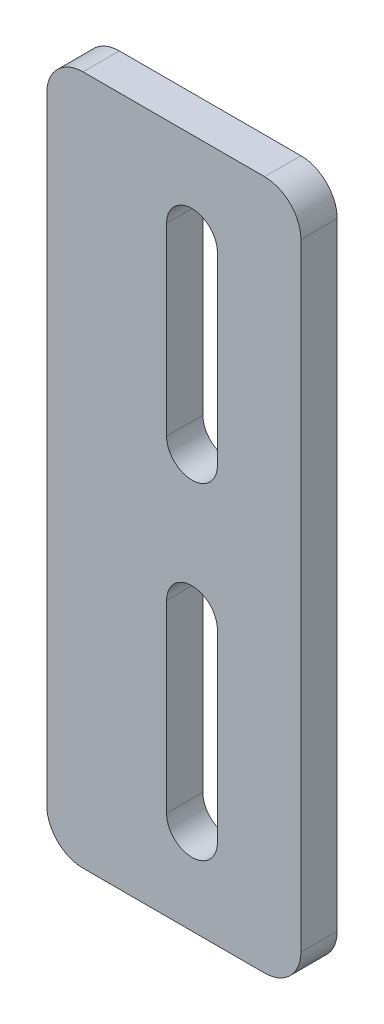
SolidWorks part; units mm, degrees
ref_plane "Front Plane" through (0, 0, 0) normal (0, 0, 1) x (1, 0, 0)
ref_plane "Top Plane" through (0, 0, 0) normal (0, 1, 0) x (1, 0, 0)
ref_plane "Right Plane" through (0, 0, 0) normal (1, 0, 0) x (0, 0, -1)
sketch "Sketch1" plane through (0, 0, 0) normal (0, 0, 1) x (1, 0, 0)
  line L0 (77.5, 30.527) -> (0, 30.527) construction
  line L1 (0, -64.473) -> (35, -64.473)
  line L2 (0, -64.473) -> (0, 30.527)
  line L3 (0, 30.527) -> (35, 30.527)
  line L4 (35, -64.473) -> (35, 30.527)
  line L5 (23.5, -7.173) -> (23.5, 18.227) construction
  line L6 (16.5, 18.227) -> (16.5, -7.173) construction
  line L7 (16.5, -26.773) -> (16.5, -52.173) construction
  line L8 (23.5, -52.173) -> (23.5, -26.773) construction
  line L9 (23.5, -7.173) -> (23.5, 18.227)
  line L10 (16.5, 18.227) -> (16.5, -7.173)
  line L11 (16.5, -26.773) -> (16.5, -52.173)
  line L12 (23.5, -52.173) -> (23.5, -26.773)
  arc A0 (23.5, 18.227) -> (16.5, 18.227) centre (20, 18.227) ccw construction
  arc A2 (16.5, -52.173) -> (23.5, -52.173) centre (20, -52.173) ccw construction
  arc A4 (23.5, 18.227) -> (16.5, 18.227) centre (20, 18.227) ccw
  arc A6 (16.5, -52.173) -> (23.5, -52.173) centre (20, -52.173) ccw
  arc A8 (23.5, -26.773) -> (16.5, -26.773) centre (20, -26.773) ccw construction
  arc A9 (23.5, -26.773) -> (16.5, -26.773) centre (20, -26.773) ccw
  arc A10 (16.5, -7.173) -> (23.5, -7.173) centre (20, -7.173) ccw construction
  arc A11 (16.5, -7.173) -> (23.5, -7.173) centre (20, -7.173) ccw
  point P19 (0, 0)
  dimension "D1" = 35
extrude "Boss-Extrude1" add sketch "Sketch1" along normal blind 5 contours L1 L4 L3 L2 A11 L10 A4 L9 A9 L12 A6 L11
fillet "Fillet1" radius 5 4 edges at (0, -64.473, 2.5) (35, -64.473, 2.5) (35, 30.527, 2.5) (0, 30.527, 2.5)
